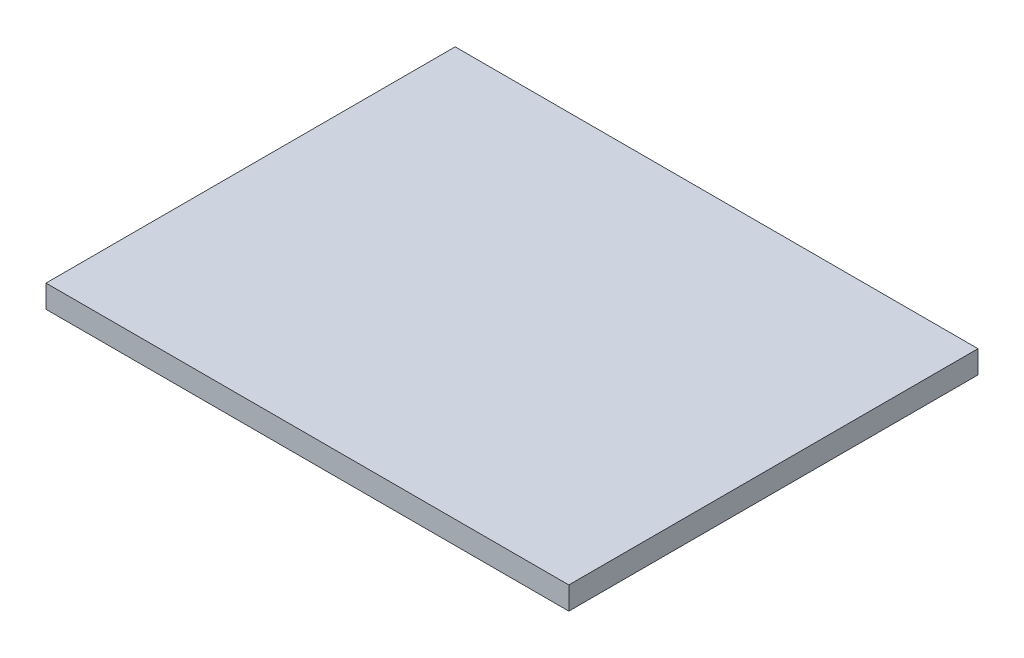
SolidWorks part; units mm, degrees
material "ABS"
ref_plane "Front Plane" through (0, 0, 0) normal (0, 0, 1) x (1, 0, 0)
ref_plane "Top Plane" through (0, 0, 0) normal (0, 1, 0) x (1, 0, 0)
ref_plane "Right Plane" through (0, 0, 0) normal (1, 0, 0) x (0, 0, -1)
sketch "Sketch1" plane through (0, 0, 0) normal (0, 1, 0) x (1, 0, 0)
  line L1 (-57.5, -45) -> (57.5, -45)
  line L2 (-57.5, -45) -> (-57.5, 45)
  line L3 (-57.5, 45) -> (57.5, 45)
  line L4 (57.5, -45) -> (57.5, 45)
  line L5 (-57.5, -45) -> (57.5, 45) construction
  line L6 (-57.5, 45) -> (57.5, -45) construction
  point P0 (0, 0)
  dimension "D1" = 115
  dimension "D2" = 90
extrude "Boss-Extrude1" add sketch "Sketch1" along normal blind 5
